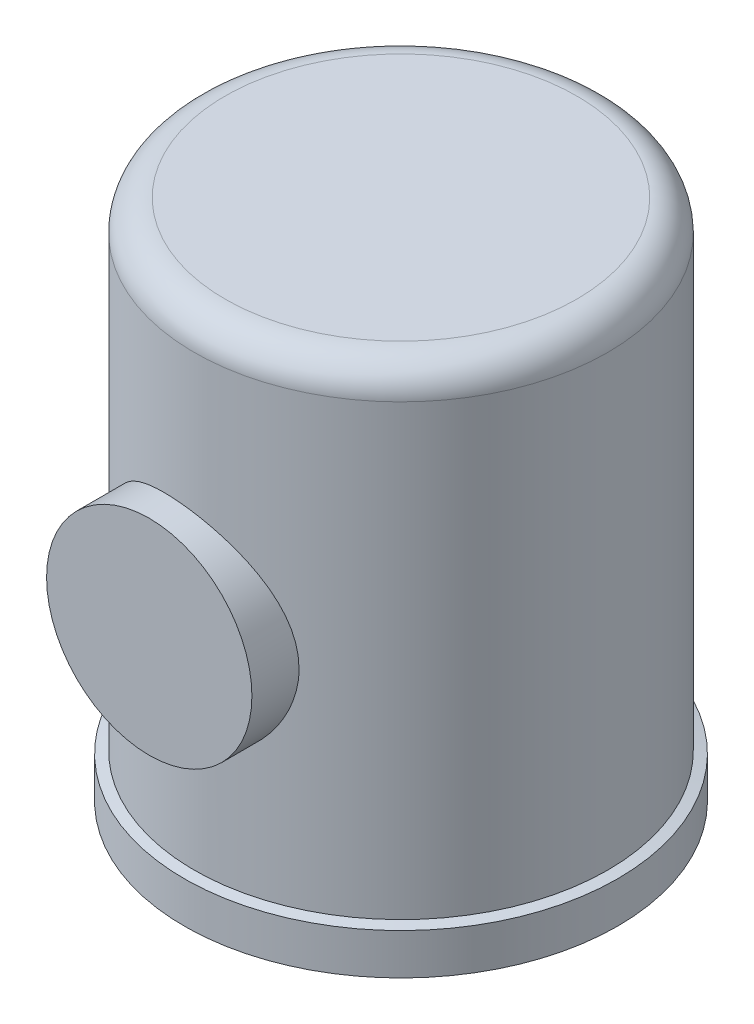
SolidWorks part; units mm, degrees
ref_plane "Front Plane" through (0, 0, 0) normal (0, 0, 1) x (1, 0, 0)
ref_plane "Top Plane" through (0, 0, 0) normal (0, 1, 0) x (1, 0, 0)
ref_plane "Right Plane" through (0, 0, 0) normal (1, 0, 0) x (0, 0, -1)
sketch "Sketch1" plane through (0, 0, 0) normal (0, 0, 1) x (1, 0, 0)
  line L0 (2.7649, 4.73) -> (2.7649, 55.2674) construction
  line L1 (20.9, 0) -> (23.8716, 0)
  line L2 (23.8716, 0) -> (23.8716, 4)
  line L3 (23.8716, 4) -> (22.9, 4.2367)
  line L4 (22.9, 4.2367) -> (22.9, 47.9082)
  line L6 (20.9, 0) -> (20.9, 11.9082)
  line L7 (18.9, 48.9082) -> (2.7649, 48.9082)
  line L8 (2.7649, 48.9082) -> (2.7649, 50.9082)
  line L9 (20.9, 13.9082) -> (20.9, 46.9082)
  line L10 (20.9, 13.9082) -> (2.7649, 13.9082)
  line L12 (20.9, 11.9082) -> (2.7649, 11.9082)
  line L13 (2.7649, 13.9082) -> (2.7649, 11.9082)
  line L14 (19.9, 50.9082) -> (2.7649, 50.9082)
  arc A1 (20.9, 46.9082) -> (18.9, 48.9082) centre (18.9, 46.9082) ccw
  arc A2 (22.9, 47.9082) -> (19.9, 50.9082) centre (19.9, 47.9082) ccw
  point P11 (22.9, 50.9082)
  dimension "D9" = 2
  dimension "D4" = 3
  dimension "D1" = 2
  dimension "D2" = 4
  dimension "D3" = 1
  dimension "D6" = 2
  dimension "D7" = 2.9716
  dimension "D10" = 2
  dimension "D11" = 11.9082
  dimension "D12" = 35
  dimension "D13" = 37
revolve "Revolve1" add sketch "Sketch1" angle 360 about L0
ref_plane "Plane1" through (0, 4, 0) normal (0, 1, 0) x (1, 0, 0)
sketch "Sketch3" plane through (0, 0, 0) normal (0, 0, 1) x (1, 0, 0)
  point P0 (1.2404, 19.1989)
ref_point "Point1"
ref_plane "Plane2" through (0, 0, 22.9) normal (0, 0, 1) x (1, 0, 0)
sketch "Sketch4" plane through (0, 0, 22.9) normal (0, 0, 1) x (1, 0, 0)
  line L0 (22.9, 36.5) -> (-22.9, 36.5) construction
  circle A1 centre (1.1446, 24.5) radius 10
  dimension "D1" = 20
  dimension "D2" = 12
extrude "Boss-Extrude2" add sketch "Sketch4" against normal blind 6
ref_plane "Plane3" through (0, 0, 16.9) normal (0, 0, -1) x (-1, 0, 0)
ref_plane "Plane4" through (0, 40, 0) normal (0, 1, 0) x (1, 0, 0)
sketch "Sketch9" plane through (0, 40, 0) normal (0, 1, 0) x (1, 0, 0)
  line L0 (-20.5, 0) -> (20.5, 0)
  arc A0 (20.5, 0) -> (-20.5, 0) centre (0, 0) ccw
  dimension "D1" = 41
extrude "Cut-Extrude2" cut sketch "Sketch9" against normal blind 30
